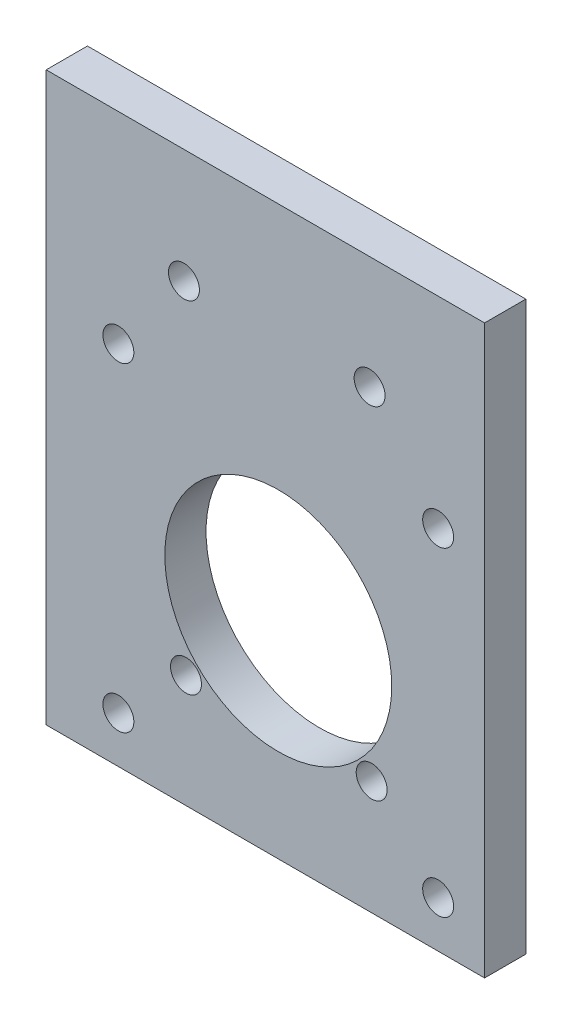
SolidWorks part; units mm, degrees
ref_plane "Front Plane" through (0, 0, 0) normal (0, 0, 1) x (1, 0, 0)
ref_plane "Top Plane" through (0, 0, 0) normal (0, 1, 0) x (1, 0, 0)
ref_plane "Right Plane" through (0, 0, 0) normal (1, 0, 0) x (0, 0, -1)
sketch "Sketch1" plane through (0, 0, 0) normal (0, 0, 1) x (1, 0, 0)
  line L1 (-21.25, 20) -> (21.25, 20)
  line L2 (-21.25, 20) -> (-21.25, -20)
  line L3 (-21.25, -20) -> (21.25, -20)
  line L4 (21.25, 20) -> (21.25, -20)
  line L5 (-21.25, 20) -> (21.25, -20) construction
  line L6 (-21.25, -20) -> (21.25, 20) construction
  point P0 (0, 0)
  dimension "D1" = 42.5
  dimension "D2" = 40
extrude "Boss-Extrude1" add sketch "Sketch1" along normal mid plane 4
sketch "Sketch2" plane through (0, 0, -2) normal (0, 0, -1) x (-1, 0, 0)
  line L0 (21.25, -20) -> (-21.25, -20) construction
  line L1 (-21.25, -20) -> (-21.25, 20) construction
  circle A0 centre (-16.75, 15.5) radius 1.5
  circle A1 centre (14.25, 15.5) radius 1.5
  circle A2 centre (14.25, -15.5) radius 1.5
  circle A3 centre (-16.75, -15.5) radius 1.5
  dimension "D1" = 3
  dimension "D2" = 31
  dimension "D3" = 31
  dimension "D4" = 4.5
  dimension "D5" = 4.5
extrude "Cut-Extrude1" cut sketch "Sketch2" against normal blind 4
sketch "Sketch3" plane through (0, 0, 2) normal (0, 0, 1) x (1, 0, 0)
  line L0 (21.25, -20) -> (21.25, 20) construction
  line L1 (-21.25, -20) -> (21.25, -20) construction
  circle A7 centre (1.25, 0) radius 11
  dimension "D2" = 20
  dimension "D1" = 20
extrude "Cut-Extrude2" cut sketch "Sketch3" against normal blind 4
sketch "Sketch4" plane through (0, 20, 0) normal (0, 1, 0) x (1, 0, 0)
  line L1 (-21.25, 2) -> (21.25, 2)
  line L2 (-21.25, 2) -> (-21.25, -2)
  line L3 (-21.25, -2) -> (21.25, -2)
  line L4 (21.25, 2) -> (21.25, -2)
extrude "Boss-Extrude2" add sketch "Sketch4" along normal blind 15
sketch "Sketch7" plane through (0, 0, 2) normal (0, 0, 1) x (1, 0, 0)
  circle A0 centre (-7.894, 23.9455) radius 1.5
  circle A1 centre (10.1057, 24.0536) radius 1.5
  circle A2 centre (10.3039, -8.9458) radius 1.5
  circle A3 centre (-7.6958, -9.0539) radius 1.5
  dimension "D1" = 3
extrude "Cut-Extrude3" cut sketch "Sketch7" against normal blind 10
